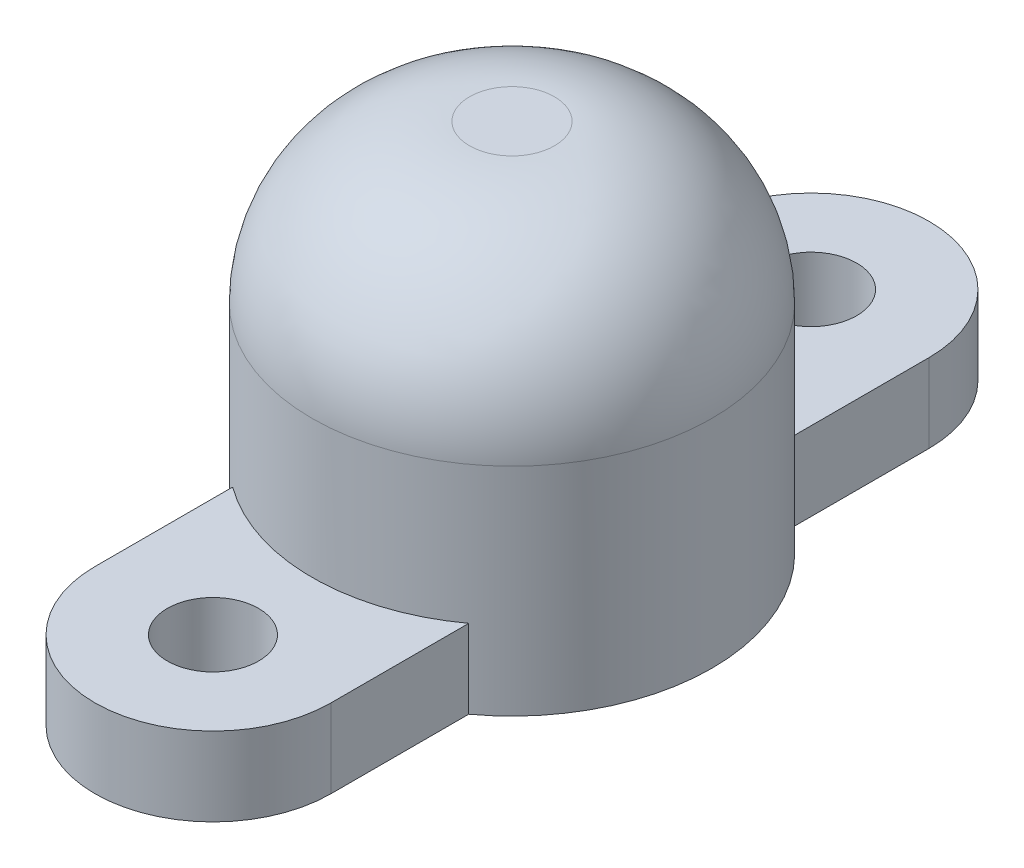
SolidWorks part; units mm, degrees
ref_plane "Front Plane" through (0, 0, 0) normal (0, 0, 1) x (1, 0, 0)
ref_plane "Top Plane" through (0, 0, 0) normal (0, 1, 0) x (1, 0, 0)
ref_plane "Right Plane" through (0, 0, 0) normal (1, 0, 0) x (0, 0, -1)
sketch "Sketch1" plane through (0, 0, 0) normal (0, 1, 0) x (1, 0, 0)
  circle A0 centre (0, 0) radius 12.7
  dimension "D1" = 25.4
extrude "Boss-Extrude1" add sketch "Sketch1" along normal blind 23.75
fillet "Fillet1" radius 10 1 edges at (0, 23.75, 12.7)
sketch "Sketch2" plane through (0, 0, 0) normal (0, -1, 0) x (1, 0, 0)
  line L0 (0, 19) -> (0, -19) construction
  line L1 (7.5, 19) -> (7.5, -19)
  line L2 (-7.5, 19) -> (-7.5, -19)
  line L3 (0, 19) -> (0, -19) construction
  arc A0 (7.5, 19) -> (-7.5, 19) centre (0, 19) ccw
  arc A1 (-7.5, -19) -> (7.5, -19) centre (0, -19) ccw
  circle A2 centre (0, 19) radius 2.9
  circle A3 centre (0, -19) radius 2.9
  point P3 (0, 0)
  point P12 (0, 0)
  point P13 (0, 0)
  dimension "D2" = 5.8
  dimension "D3" = 5.8
  dimension "D1" = 15
  dimension "D4" = 19
  dimension "D5" = 19
extrude "Boss-Extrude2" add sketch "Sketch2" against normal blind 5
